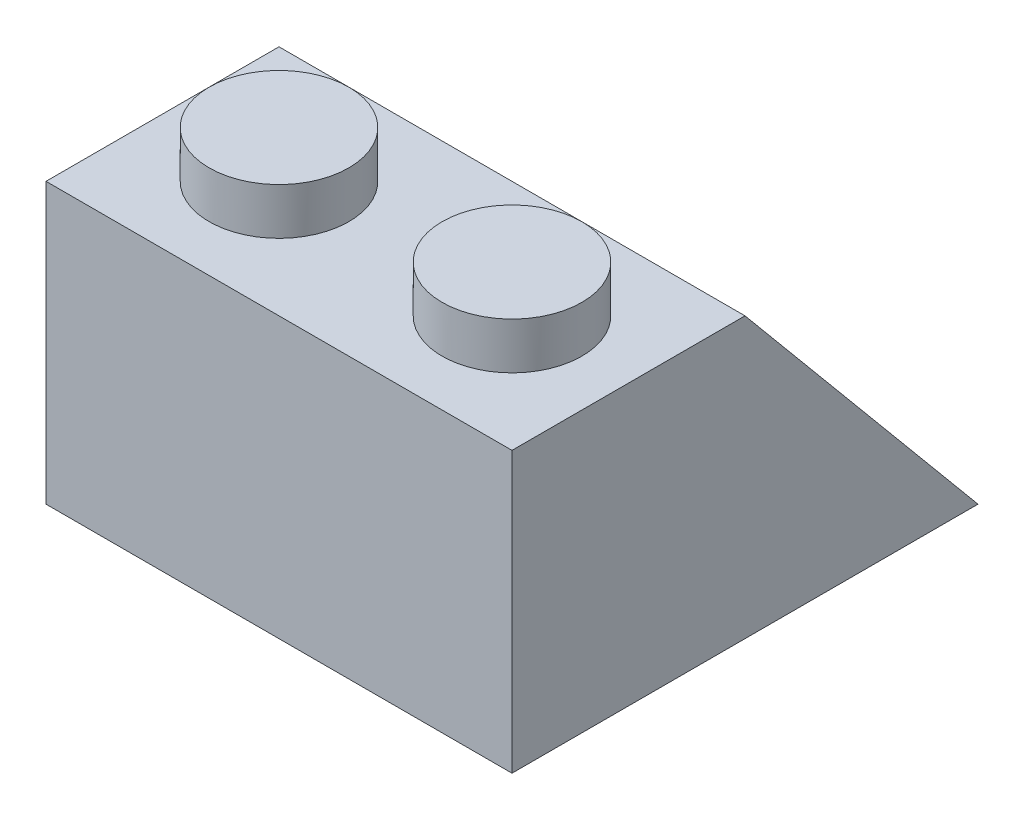
SolidWorks part; units mm, degrees
ref_plane "Front Plane" through (0, 0, 0) normal (0, 0, 1) x (1, 0, 0)
ref_plane "Top Plane" through (0, 0, 0) normal (0, 1, 0) x (1, 0, 0)
ref_plane "Right Plane" through (0, 0, 0) normal (1, 0, 0) x (0, 0, -1)
sketch "Sketch1" plane through (0, 0, 0) normal (1, 0, 0) x (0, 0, -1)
  line L0 (0, 0) -> (16, 0)
  line L1 (16, 0) -> (8, 9.6)
  line L2 (8, 9.6) -> (0, 9.6)
  line L3 (0, 9.6) -> (0, 0)
  dimension "D1" = 9.6
  dimension "D2" = 8
  dimension "D3" = 16
extrude "Boss-Extrude1" add sketch "Sketch1" along normal blind 16
sketch "Sketch2" plane through (0, 9.6, 0) normal (0, 1, 0) x (1, 0, 0)
  line L0 (0, 4) -> (4, 4) construction
  line L1 (0, 8) -> (0, 0) construction
  circle A0 centre (4, 4) radius 2.4
  dimension "D2" = 4.8
  dimension "D1" = 4
extrude "Boss-Extrude2" add sketch "Sketch2" along normal blind 1.6
pattern_linear "LPattern1" count 2 spacing 8 along (1, 0, 0) of "Boss-Extrude2"
shell "Shell1" thickness 1.6
